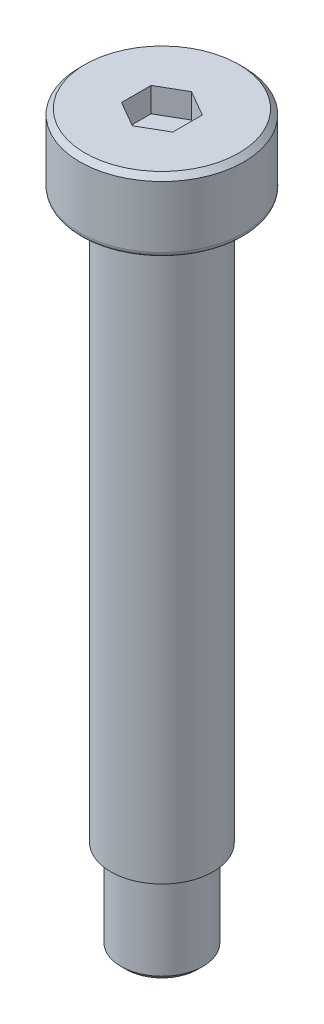
SolidWorks part; units mm, degrees
material "Plain Carbon Steel"
ref_plane "Front Plane" through (0, 0, 0) normal (0, 0, 1) x (1, 0, 0)
ref_plane "Top Plane" through (0, 0, 0) normal (0, 1, 0) x (1, 0, 0)
ref_plane "Right Plane" through (0, 0, 0) normal (1, 0, 0) x (0, 0, -1)
sketch "Sketch1" plane through (0, 0, 0) normal (0, 0, 1) x (1, 0, 0)
  line L0 (0, 0) -> (8, 0)
  line L1 (8, 0) -> (8, -7)
  line L2 (8, -7) -> (4.75, -7)
  line L3 (4.75, -7) -> (4.75, -7.5)
  line L4 (4.75, -7.5) -> (5, -7.5)
  line L5 (5, -7.5) -> (5, -62)
  line L6 (5, -62) -> (4, -62)
  line L7 (4, -62) -> (4, -71)
  line L8 (4, -71) -> (0, -71)
  line L9 (0, -71) -> (0, 0)
  line L10 (0, 5) -> (0, -76) construction
  dimension "D1" = 5
  dimension "D2" = 5
  dimension "D3" = 8
  dimension "D4" = 10
  dimension "D5" = 0.25
  dimension "D6" = 16
  dimension "Length" = 55
  dimension "D8" = 7
  dimension "D9" = 0.5
  dimension "D10" = 9
revolve "Revolve1" add sketch "Sketch1" angle 360 about L10
sketch "Sketch2" plane through (0, 0, 0) normal (0, 1, 0) x (1, 0, 0)
  line L1 (0, -2.8868) -> (2.5, -1.4434)
  line L2 (2.5, -1.4434) -> (2.5, 1.4434)
  line L3 (2.5, 1.4434) -> (0, 2.8868)
  line L4 (0, 2.8868) -> (-2.5, 1.4434)
  line L5 (-2.5, 1.4434) -> (-2.5, -1.4434)
  line L6 (-2.5, -1.4434) -> (0, -2.8868)
  circle A0 centre (0, 0) radius 2.5 construction
  dimension "D1" = 5
extrude "Cut-Extrude1" cut sketch "Sketch2" against normal blind 2.4
chamfer "Chamfer1" distance 0.5 angle 45 1 edges at (-8, 0, 0)
fillet "Fillet1" radius 0.5 1 edges at (-8, -7, 0)
chamfer "Chamfer2" distance 0.5 angle 45 1 edges at (-4, -71, 0)
